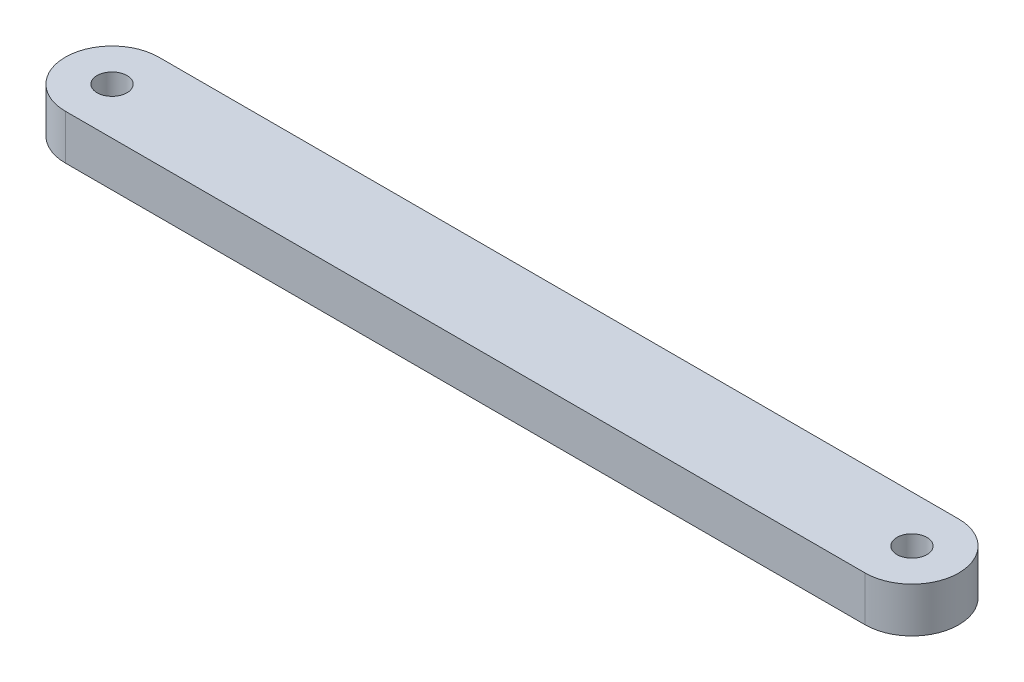
SolidWorks part; units mm, degrees
ref_plane "正面" through (0, 0, 0) normal (0, 0, 1) x (1, 0, 0)
ref_plane "平面" through (0, 0, 0) normal (0, 1, 0) x (1, 0, 0)
ref_plane "右側面" through (0, 0, 0) normal (1, 0, 0) x (0, 0, -1)
sketch "ｽｹｯﾁ1" plane through (0, 0, 0) normal (0, 1, 0) x (1, 0, 0)
  line L0 (-42.75, 0) -> (42.75, 0) construction
  line L5 (-42.75, 5) -> (42.75, 5)
  line L6 (-42.75, -5) -> (42.75, -5)
  arc A4 (-42.75, 5) -> (-42.75, -5) centre (-42.75, 0) ccw
  arc A5 (42.75, -5) -> (42.75, 5) centre (42.75, 0) ccw
  circle A6 centre (-42.75, 0) radius 1.6
  circle A7 centre (42.75, 0) radius 1.6
  point P2 (0, 0)
  dimension "D3" = 3.2
  dimension "D1" = 85.5
  dimension "D2" = 10
extrude "ﾎﾞｽ - 押し出し1" add sketch "ｽｹｯﾁ1" along normal blind 4.8
